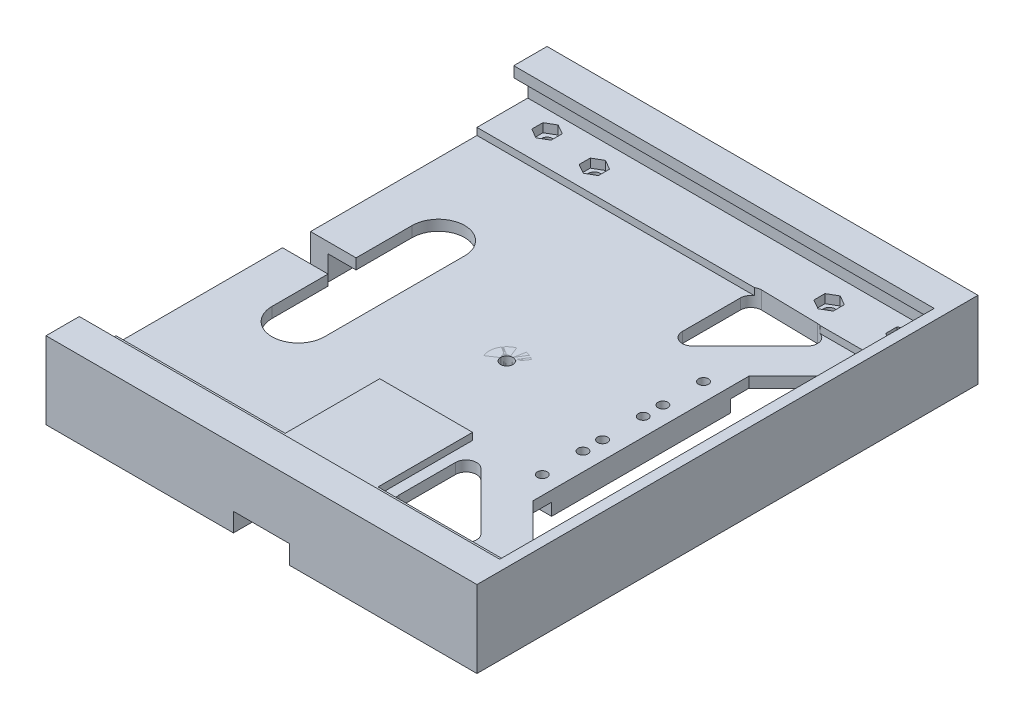
SolidWorks part; units mm, degrees
ref_plane "Front Plane" through (0, 0, 0) normal (0, 0, 1) x (1, 0, 0)
ref_plane "Top Plane" through (0, 0, 0) normal (0, 1, 0) x (1, 0, 0)
ref_plane "Right Plane" through (0, 0, 0) normal (1, 0, 0) x (0, 0, -1)
sketch "Sketch1" plane through (0, 0, 0) normal (0, 1, 0) x (1, 0, 0)
  line L1 (-60, -10) -> (60, -10)
  line L2 (-60, -10) -> (-60, 10)
  line L3 (-60, 10) -> (60, 10)
  line L4 (60, -10) -> (60, 10)
  line L5 (-60, -10) -> (60, 10) construction
  line L6 (-60, 10) -> (60, -10) construction
  point P0 (0, 0)
  dimension "D1" = 120
  dimension "D2" = 20
extrude "Boss-Extrude1" add sketch "Sketch1" along normal blind 12 contours L3 L4 L1 L2
sketch "Sketch2" plane through (0, 12, 0) normal (0, 1, 0) x (1, 0, 0)
  line L0 (60, -10) -> (60, 10) construction
  line L1 (-60, 10) -> (60, 10)
  line L2 (-60, 10) -> (-60, 0.5)
  line L3 (-60, 0.5) -> (60, 0.5)
  line L4 (60, 10) -> (60, 0.5)
  dimension "D1" = 9.5
extrude "Boss-Extrude2" add sketch "Sketch2" along normal blind 10
sketch "Sketch3" plane through (60, 0, 0) normal (1, 0, 0) x (0, 0, -1)
  line L0 (0.5, 22) -> (10, 22) construction
  line L1 (0.5, 12) -> (4.5, 12)
  line L2 (0.5, 12) -> (0.5, 19)
  line L3 (0.5, 19) -> (4.5, 19)
  line L4 (4.5, 12) -> (4.5, 19)
  dimension "D1" = 4
  dimension "D2" = 3
extrude "Cut-Extrude1" cut sketch "Sketch3" against normal up to next
sketch "Sketch4" plane through (0, 0, 0) normal (0, -1, 0) x (1, 0, 0)
  line L0 (-60, 10) -> (60, 10) construction
  line L1 (-38, 10) -> (38, 10)
  line L2 (-38, 10) -> (-38, -10)
  line L3 (-38, -10) -> (38, -10)
  line L4 (38, 10) -> (38, -10)
  line L5 (60, 10) -> (60, -10) construction
  line L6 (-60, 10) -> (-60, -10) construction
  line L8 (-60, -10) -> (60, -10) construction
  dimension "D1" = 22
  dimension "D2" = 22
extrude "Cut-Extrude2" cut sketch "Sketch4" against normal blind 7
sketch "Sketch7" plane through (0, 0, 10) normal (0, 0, 1) x (1, 0, 0)
  line L0 (60, 12) -> (60, 0) construction
  line L1 (-60, 0) -> (60, 0)
  line L2 (-60, 0) -> (-60, 10)
  line L3 (-60, 10) -> (60, 10)
  line L4 (60, 0) -> (60, 10)
  dimension "D1" = 10
extrude "Boss-Extrude3" add sketch "Sketch7" along normal blind 123
sketch "Sketch20" plane through (0, 10, 0) normal (0, -1, 0) x (1, 0, 0)
  line L2 (60, 133) -> (60, -10) construction
  line L4 (-60, -10) -> (-38, -10) construction
  circle A0 centre (0, 61.5) radius 5
  dimension "D3" = 10
  dimension "D1" = 60
  dimension "D2" = 71.5
sketch "Sketch8" plane through (0, 10, 0) normal (0, 1, 0) x (1, 0, 0)
  line L0 (60, -133) -> (60, -10) construction
  line L1 (-60, -133) -> (60, -133)
  line L2 (-60, -133) -> (-60, -113)
  line L3 (-60, -113) -> (60, -113)
  line L4 (60, -133) -> (60, -113)
  dimension "D1" = 20
extrude "Boss-Extrude4" add sketch "Sketch8" along normal blind 2
sketch "Sketch10" plane through (0, 12, 0) normal (0, 1, 0) x (1, 0, 0)
  line L1 (-60, -133) -> (60, -133)
  line L2 (-60, -133) -> (-60, -126.5)
  line L3 (-60, -126.5) -> (60, -126.5)
  line L4 (60, -133) -> (60, -126.5)
  dimension "D1" = 6.5
extrude "Boss-Extrude5" add sketch "Sketch10" along normal blind 7 separate body
sketch "Sketch11" plane through (0, 19, 0) normal (0, 1, 0) x (1, 0, 0)
  line L1 (-60, -133) -> (60, -133)
  line L2 (-60, -133) -> (-60, -123.5)
  line L3 (-60, -123.5) -> (60, -123.5)
  line L4 (60, -133) -> (60, -123.5)
  line L5 (60, -133) -> (60, -126.5) construction
  dimension "D1" = 9.5
extrude "Boss-Extrude6" add sketch "Sketch11" along normal blind 3
sketch "Sketch13" plane through (60, 0, 0) normal (1, 0, 0) x (0, 0, -1)
  line L1 (10, 0) -> (-133, 0)
  line L2 (10, 0) -> (10, 22)
  line L3 (10, 22) -> (-133, 22)
  line L4 (-133, 0) -> (-133, 22)
extrude "Boss-Extrude7" add sketch "Sketch13" along normal blind 3
sketch "Sketch14" plane through (0, 0, 0) normal (0, -1, 0) x (1, 0, 0)
  line L0 (-38, 10) -> (-55, 10)
  line L1 (-55, 10) -> (-55, 115)
  line L2 (-55, 115) -> (58, 115)
  line L3 (58, 115) -> (58, 10)
  line L4 (58, 10) -> (38, 10)
  line L6 (-60, 133) -> (63, 133) construction
  line L7 (-60, 133) -> (-60, -10) construction
  line L8 (63, 133) -> (63, -10) construction
  line L9 (-38, 10) -> (38, 10)
  dimension "D1" = 18
  dimension "D2" = 5
  dimension "D3" = 5
extrude "Cut-Extrude5" cut sketch "Sketch14" against normal blind 7
sketch "Sketch16" plane through (0, 0, 115) normal (0, 0, -1) x (-1, 0, 0)
  line L0 (-58, 0) -> (55, 0) construction
  line L1 (8.9, 7) -> (-11.9, 7)
  line L2 (8.9, 7) -> (8.9, 5.35)
  line L3 (8.9, 5.35) -> (-11.9, 5.35)
  line L4 (-11.9, 7) -> (-11.9, 5.35)
  line L6 (-58, 7) -> (55, 7) construction
  point P4 (-1.5, 5.35)
  point P7 (-1.5, 0)
  dimension "D1" = 1.65
  dimension "D2" = 20.8
extrude "Cut-Extrude6" cut sketch "Sketch16" against normal blind 16.5
sketch "Sketch17" plane through (0, 0, 115) normal (0, 0, -1) x (-1, 0, 0)
  line L0 (-11.9, 5.35) -> (8.9, 5.35) construction
  line L1 (6.5, 5.35) -> (-9.5, 5.35)
  line L2 (6.5, 5.35) -> (6.5, 0)
  line L3 (6.5, 0) -> (-9.5, 0)
  line L4 (-9.5, 5.35) -> (-9.5, 0)
  line L5 (-58, 0) -> (55, 0) construction
  point P8 (-1.5, 0)
  dimension "D1" = 16
extrude "Cut-Extrude7" cut sketch "Sketch17" against normal through all
sketch "Sketch18" plane through (0, 7, 0) normal (0, -1, 0) x (1, 0, 0)
  line L0 (-6.5, 115) -> (-55, 115) construction
  line L1 (-6.5, 131.5) -> (9.5, 131.5)
  line L2 (-6.5, 131.5) -> (-6.5, 115)
  line L4 (9.5, 131.5) -> (9.5, 115)
  line L5 (-8.75, 115) -> (-6.5, 115)
  line L6 (-8.75, 115) -> (-8.75, 89)
  line L7 (-8.75, 89) -> (11.75, 89)
  line L8 (11.75, 115) -> (11.75, 89)
  line L9 (58, 115) -> (9.5, 115) construction
  line L10 (9.5, 115) -> (11.75, 115)
  dimension "D1" = 20.5
  dimension "D2" = 0
  dimension "D3" = 26
  dimension "D4" = 2.25
  dimension "D5" = 2.25
extrude "Cut-Extrude8" cut sketch "Sketch18" against normal blind 2.75
sketch "Sketch19" plane through (0, 7, 0) normal (0, -1, 0) x (1, 0, 0)
  line L1 (-60, 133) -> (-60, -10) construction
  line L2 (-47, 57.5) -> (-60, 57.5)
  line L3 (-47, 65.5) -> (-60, 65.5)
  line L4 (-47, 65.5) -> (-47, 81.5)
  line L5 (-47, 41.5) -> (-47, 57.5)
  line L6 (-32, 41.5) -> (-32, 81.5)
  arc A1 (-60, 65.5) -> (-60, 57.5) centre (-60, 61.5) ccw
  arc A2 (-47, 41.5) -> (-32, 41.5) centre (-39.5, 41.5) ccw
  arc A3 (-32, 81.5) -> (-47, 81.5) centre (-39.5, 81.5) ccw
  point P4 (-49.75, 61.5)
  point P10 (-60, 61.5)
  point P12 (-39.5, 61.5)
  dimension "D1" = 8
  dimension "D2" = 15
  dimension "D3" = 28
  dimension "D4" = 40
extrude "Cut-Extrude9" cut sketch "Sketch19" against normal through all both and the other way through all
sketch "Sketch22" plane through (0, 10, 0) normal (0, 1, 0) x (1, 0, 0)
  line L0 (-11.75, -86) -> (-11.75, -117)
  line L5 (-11.75, -117) -> (14.75, -117)
  line L6 (14.75, -86) -> (14.75, -117)
  line L7 (-11.75, -86) -> (14.75, -86)
  line L8 (-8.75, -115) -> (-8.75, -89) construction
  line L9 (-8.75, -89) -> (11.75, -89) construction
  line L10 (11.75, -89) -> (11.75, -115) construction
  dimension "D1" = 26.5
  dimension "D2" = 31
  dimension "D3" = 3
  dimension "D4" = 3
  dimension "D5" = 3
extrude "Boss-Extrude8" add sketch "Sketch22" along normal blind 2
sketch "Sketch27" plane through (0, 7, 0) normal (0, -1, 0) x (1, 0, 0)
  line L3 (-38, 10) -> (-38, -10) construction
  line L4 (-38, -10) -> (38, -10) construction
  line L5 (38, -10) -> (38, 10) construction
  circle A4 centre (33.5, 3) radius 1.75
  circle A6 centre (-33.5, 3) radius 1.75
  dimension "D3" = 4.5
  dimension "D7" = 3.5
  dimension "D8" = 3.5
  dimension "D1" = 4.5
  dimension "D2" = 13
extrude "Cut-Extrude11" cut sketch "Sketch27" against normal up to next
extrude "Boss-Extrude9" add sketch "Sketch20" along normal blind 8 separate body
sketch "Sketch29" plane through (0, 2, 0) normal (0, -1, 0) x (1, 0, 0)
  line L1 (2.75, 63.0877) -> (0, 64.6754)
  line L2 (0, 64.6754) -> (-2.75, 63.0877)
  line L3 (-2.75, 63.0877) -> (-2.75, 59.9123)
  line L4 (-2.75, 59.9123) -> (0, 58.3246)
  line L5 (0, 58.3246) -> (2.75, 59.9123)
  line L6 (2.75, 59.9123) -> (2.75, 63.0877)
  circle A0 centre (0, 61.5) radius 2.75 construction
  dimension "D1" = 5.5
extrude "Cut-Extrude13" cut sketch "Sketch29" against normal blind 2.5
sketch "Sketch31" plane through (0, 2, 0) normal (0, -1, 0) x (1, 0, 0)
  circle A0 centre (0, 61.5) radius 1.75
  dimension "D1" = 3.5
extrude "Cut-Extrude14" cut sketch "Sketch31" against normal through all both and the other way through all
sketch "Sketch32" plane through (0, 7, 0) normal (0, -1, 0) x (1, 0, 0)
  line L0 (63, 133) -> (63, -10) construction
  line L1 (28, 87) -> (38.3, 87)
  line L2 (28, 87) -> (28, 36)
  line L3 (28, 36) -> (38.3, 36)
  line L4 (38.3, 87) -> (38.3, 36)
  line L5 (-32, 41.5) -> (-32, 81.5) construction
  point P6 (28, 61.5)
  point P9 (-32, 61.5)
  dimension "D1" = 10.3
  dimension "D2" = 51
  dimension "D3" = 35
extrude "Boss-Extrude10" add sketch "Sketch32" along normal blind 3.5
sketch "Sketch33" plane through (0, 3.5, 0) normal (0, -1, 0) x (1, 0, 0)
  line L0 (28, 36) -> (38.3, 36) construction
  line L1 (28, 36) -> (38.3, 36) construction
  line L2 (38.3, 87) -> (28, 87) construction
  circle A0 centre (33.15, 38.5) radius 1.4
  circle A1 centre (33.15, 50.1) radius 1.4
  circle A2 centre (33.15, 72.9) radius 1.4
  circle A3 centre (33.15, 84.5) radius 1.4
  circle A4 centre (33.15, 55.7) radius 1.4
  circle A5 centre (33.15, 67.3) radius 1.4
  point P6 (33.15, 36)
  point P20 (33.15, 87)
  dimension "D1" = 2.8
  dimension "D2" = 2.8
  dimension "D5" = 2.8
  dimension "D6" = 2.8
  dimension "D9" = 2.8
  dimension "D10" = 2.8
  dimension "D3" = 11.6
  dimension "D4" = 2.5
  dimension "D7" = 11.6
  dimension "D8" = 2.5
  dimension "D11" = 11.6
  dimension "D12" = 5.6
extrude "Cut-Extrude15" cut sketch "Sketch33" against normal through all
sketch "Sketch38" plane through (0, 0, 0) normal (0, -1, 0) x (1, 0, 0)
  line L1 (-60, 133) -> (-6.5, 133) construction
  line L2 (-60, 133) -> (-60, 65.5) construction
  line L3 (9.5, 133) -> (63, 133) construction
  line L4 (63, 133) -> (63, -10) construction
  line L5 (-60, 57.5) -> (-60, -10) construction
  line L6 (-60, -10) -> (-38, -10) construction
  line L7 (38, -10) -> (63, -10) construction
  circle A0 centre (-49, 122) radius 1.55
  circle A1 centre (52, 122) radius 1.55
  circle A2 centre (52, 1) radius 1.55
  circle A3 centre (-49, 1) radius 1.55
  dimension "D1" = 3.1
  dimension "D2" = 3.1
  dimension "D3" = 3.1
  dimension "D4" = 3.1
  dimension "D5" = 11
  dimension "D6" = 11
  dimension "D7" = 11
  dimension "D8" = 11
  dimension "D9" = 11
  dimension "D10" = 11
  dimension "D11" = 11
  dimension "D12" = 11
extrude "Cut-Extrude19" cut sketch "Sketch38" against normal up to next (12 mm away)
sketch "Sketch39" plane through (0, 12, 0) normal (0, 1, 0) x (1, 0, 0)
  line L1 (-46.25, -2.5877) -> (-46.25, 0.5877)
  line L2 (-46.25, 0.5877) -> (-49, 2.1754)
  line L3 (-49, 2.1754) -> (-51.75, 0.5877)
  line L4 (-51.75, 0.5877) -> (-51.75, -2.5877)
  line L5 (-51.75, -2.5877) -> (-49, -4.1754)
  line L6 (-49, -4.1754) -> (-46.25, -2.5877)
  line L7 (-30.75, -4.5877) -> (-30.75, -1.4123)
  line L8 (-30.75, -1.4123) -> (-33.5, 0.1754)
  line L9 (-33.5, 0.1754) -> (-36.25, -1.4123)
  line L10 (-36.25, -1.4123) -> (-36.25, -4.5877)
  line L11 (-36.25, -4.5877) -> (-33.5, -6.1754)
  line L12 (-33.5, -6.1754) -> (-30.75, -4.5877)
  line L13 (33.5, -6.1754) -> (36.25, -4.5877)
  line L14 (36.25, -4.5877) -> (36.25, -1.4123)
  line L15 (36.25, -1.4123) -> (33.5, 0.1754)
  line L16 (33.5, 0.1754) -> (30.75, -1.4123)
  line L17 (30.75, -1.4123) -> (30.75, -4.5877)
  line L18 (30.75, -4.5877) -> (33.5, -6.1754)
  line L19 (52, -4.1754) -> (54.75, -2.5877)
  line L20 (54.75, -2.5877) -> (54.75, 0.5877)
  line L21 (54.75, 0.5877) -> (52, 2.1754)
  line L22 (52, 2.1754) -> (49.25, 0.5877)
  line L23 (49.25, 0.5877) -> (49.25, -2.5877)
  line L24 (49.25, -2.5877) -> (52, -4.1754)
  line L25 (54.75, -120.4123) -> (52, -118.8246)
  line L26 (52, -118.8246) -> (49.25, -120.4123)
  line L27 (49.25, -120.4123) -> (49.25, -123.5877)
  line L28 (49.25, -123.5877) -> (52, -125.1754)
  line L29 (52, -125.1754) -> (54.75, -123.5877)
  line L30 (54.75, -123.5877) -> (54.75, -120.4123)
  line L31 (-46.25, -120.4123) -> (-49, -118.8246)
  line L32 (-49, -118.8246) -> (-51.75, -120.4123)
  line L33 (-51.75, -120.4123) -> (-51.75, -123.5877)
  line L34 (-51.75, -123.5877) -> (-49, -125.1754)
  line L35 (-49, -125.1754) -> (-46.25, -123.5877)
  line L36 (-46.25, -123.5877) -> (-46.25, -120.4123)
  circle A0 centre (-49, -1) radius 2.75 construction
  circle A1 centre (-33.5, -3) radius 2.75 construction
  circle A2 centre (33.5, -3) radius 2.75 construction
  circle A3 centre (52, -1) radius 2.75 construction
  circle A4 centre (52, -122) radius 2.75 construction
  circle A5 centre (-49, -122) radius 2.75 construction
  dimension "D1" = 5.5
  dimension "D2" = 5.5
  dimension "D3" = 5.5
  dimension "D4" = 5.5
  dimension "D5" = 5.5
  dimension "D6" = 5.5
extrude "Cut-Extrude20" cut sketch "Sketch39" against normal blind 2.5
sketch "Sketch40" plane through (0, 10, 0) normal (0, 1, 0) x (1, 0, 0)
  line L0 (50, -104) -> (50, -19)
  line L1 (50, -104) -> (27.7803, -81.8164) construction
  line L2 (50, -19) -> (38.3, -30.6809)
  line L3 (50, -19) -> (27.7803, -41.1836) construction
  line L4 (38.3, -30.6809) -> (38.3, -92.3191)
  line L5 (38.3, -92.3191) -> (50, -104)
  line L15 (17.75, -93.874) -> (17.75, -110)
  line L19 (20.75, -113) -> (36.9023, -113)
  line L22 (38.3, -36) -> (38.3, -87) construction
  line L23 (39.0219, -107.877) -> (22.8696, -91.7509)
  line L24 (14.75, -113) -> (14.75, -86) construction
  line L25 (17.75, -12.5573) -> (17.75, -29.126)
  line L26 (60, -113) -> (14.75, -113) construction
  line L27 (-37.4031, -9.5) -> (37.4031, -9.5) construction
  line L28 (22.8696, -31.2491) -> (39.1564, -14.9888)
  line L29 (-60, -10) -> (60, -10) construction
  line L30 (37.0936, -9.8663) -> (20.8068, -9.5579)
  arc A0 (39.1564, -14.9888) -> (37.0936, -9.8663) centre (37.0368, -12.8658) ccw
  arc A1 (20.8068, -9.5579) -> (17.75, -12.5573) centre (20.75, -12.5573) ccw
  arc A2 (17.75, -29.126) -> (22.8696, -31.2491) centre (20.75, -29.126) ccw
  arc A3 (17.75, -110) -> (20.75, -113) centre (20.75, -110) ccw
  arc A4 (36.9023, -113) -> (39.0219, -107.877) centre (36.9023, -110) ccw
  arc A5 (22.8696, -91.7509) -> (17.75, -93.874) centre (20.75, -93.874) ccw
  point P27 (44.1533, -10)
  point P30 (17.75, -9.5)
  point P39 (17.75, -86.6397)
  dimension "D4" = 3
  dimension "D1" = 3
  dimension "D2" = 10.5
  dimension "D3" = 10.5
extrude "Cut-Extrude21" cut sketch "Sketch40" against normal through all both and the other way through all
